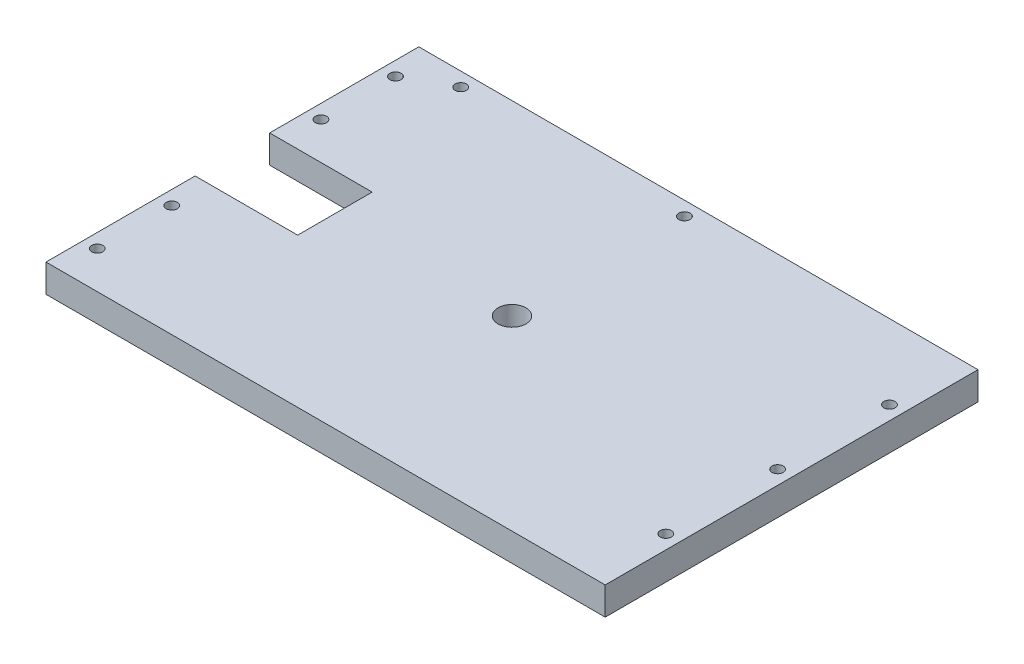
SolidWorks part; units mm, degrees
ref_plane "Front Plane" through (0, 0, 0) normal (0, 0, 1) x (1, 0, 0)
ref_plane "Top Plane" through (0, 0, 0) normal (0, 1, 0) x (1, 0, 0)
ref_plane "Right Plane" through (0, 0, 0) normal (1, 0, 0) x (0, 0, -1)
sketch "Sketch2" plane through (0, 0, 0) normal (0, 1, 0) x (1, 0, 0)
  line L0 (-168.0328, 40.5738) -> (131.9672, 40.5738)
  line L1 (131.9672, 40.5738) -> (131.9672, -159.4262)
  line L2 (131.9672, -159.4262) -> (-168.0328, -159.4262)
  line L3 (-168.0328, -159.4262) -> (-168.0328, -79.4262)
  line L4 (-168.0328, -79.4262) -> (-113.0328, -79.4262)
  line L5 (-113.0328, -79.4262) -> (-113.0328, -39.4262)
  line L6 (-113.0328, -39.4262) -> (-168.0328, -39.4262)
  line L7 (-168.0328, -39.4262) -> (-168.0328, 40.5738)
  line L8 (-168.0328, 0.5738) -> (131.9672, 0.5738) construction
  line L9 (-168.0328, -119.4262) -> (171.285, -119.4262) construction
  line L10 (-176.8442, -59.4262) -> (131.9672, -59.4262) construction
  circle A0 centre (-18.0328, -59.4262) radius 7.5
  circle A1 centre (-160.5328, 20.5738) radius 3
  circle A2 centre (-160.5328, -19.4262) radius 3
  circle A3 centre (-160.5328, -139.4262) radius 3
  circle A4 centre (-160.5328, -99.4262) radius 3
  circle A5 centre (124.4672, -119.4262) radius 3
  circle A6 centre (124.4672, 0.5738) radius 3
  circle A7 centre (124.4672, -59.4262) radius 3
  circle A8 centre (-18.0328, 33.0738) radius 3
  circle A9 centre (-138.0328, 33.0738) radius 3
  dimension "D6" = 15
  dimension "D9" = 6
  dimension "D11" = 6
  dimension "D13" = 20
  dimension "D14" = 6
  dimension "D16" = 6
  dimension "D18" = 6
  dimension "D20" = 6
  dimension "D1" = 300
  dimension "D2" = 200
  dimension "D3" = 40
  dimension "D4" = 80
  dimension "D5" = 55
  dimension "D7" = 100
  dimension "D8" = 150
  dimension "D10" = 7.5
  dimension "D12" = 20
  dimension "D15" = 7.5
  dimension "D17" = 308.8115
  dimension "D19" = 7.5
  dimension "D21" = 30
extrude "Boss-Extrude2" add sketch "Sketch2" along normal blind 15
